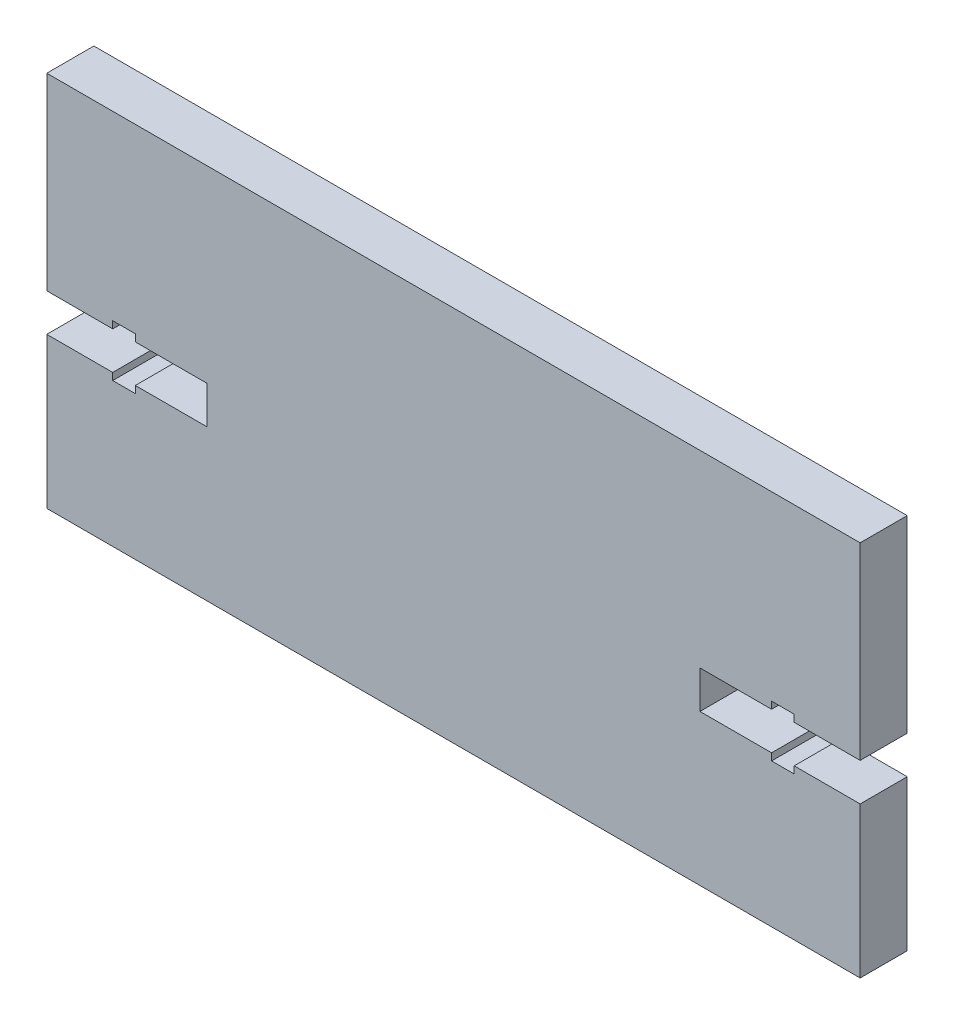
SolidWorks part; units mm, degrees
ref_plane "Front Plane" through (0, 0, 0) normal (0, 0, 1) x (1, 0, 0)
ref_plane "Top Plane" through (0, 0, 0) normal (0, 1, 0) x (1, 0, 0)
ref_plane "Right Plane" through (0, 0, 0) normal (1, 0, 0) x (0, 0, -1)
sketch "Sketch1" plane through (0, 0, 0) normal (0, 0, 1) x (1, 0, 0)
  line L1 (-34.7186, 10.5285) -> (51.6079, 10.5285)
  line L2 (-34.7186, 10.5285) -> (-34.7186, -29.4715)
  line L3 (-34.7186, -29.4715) -> (51.6079, -29.4715)
  line L4 (51.6079, 10.5285) -> (51.6079, -29.4715)
  line L7 (-34.7186, -29.4715) -> (-34.7186, 10.5285) construction
  line L8 (-39.7186, 10.5285) -> (-34.7186, 10.5285) construction
extrude "Boss-Extrude1" add sketch "Sketch1" along normal blind 5
sketch "Sketch2" plane through (0, 0, 0) normal (0, 0, -1) x (-1, 0, 0)
  line L9 (-8.4447, 10.5285) -> (-8.4447, -29.4715) construction
  line L10 (-51.6079, 10.5285) -> (34.7186, 10.5285) construction
  line L50 (34.7186, -29.4715) -> (-51.6079, -29.4715) construction
  line L51 (-51.6079, -29.4715) -> (-51.6079, 10.5285) construction
  line L52 (-51.6079, -9.4715) -> (34.7186, -9.4715) construction
  line L53 (34.7186, 10.5285) -> (34.7186, -29.4715) construction
  line L54 (-51.6079, -9.4715) -> (-44.6079, -9.4715)
  line L55 (-34.6079, -9.4715) -> (-34.6079, -13.4715)
  line L56 (-34.6079, -13.4715) -> (-42.2079, -13.4715)
  line L57 (-44.6079, -9.4715) -> (-44.6079, -8.7215)
  line L58 (-44.6079, -8.7215) -> (-42.2079, -8.7215)
  line L59 (-42.2079, -8.7215) -> (-42.2079, -9.4715)
  line L60 (-42.2079, -13.4715) -> (-42.2079, -14.2215)
  line L61 (-42.2079, -14.2215) -> (-44.6079, -14.2215)
  line L62 (-44.6079, -14.2215) -> (-44.6079, -13.4715)
  line L63 (-42.2079, -9.4715) -> (-34.6079, -9.4715)
  line L64 (-44.6079, -13.4715) -> (-51.6079, -13.4715)
  line L65 (-51.6079, -9.4715) -> (-51.6079, -13.4715)
  line L66 (34.7186, -9.4715) -> (34.7186, -13.4715)
  line L67 (27.7186, -13.4715) -> (34.7186, -13.4715)
  line L68 (25.3186, -9.4715) -> (17.7186, -9.4715)
  line L69 (27.7186, -14.2215) -> (27.7186, -13.4715)
  line L70 (25.3186, -14.2215) -> (27.7186, -14.2215)
  line L71 (25.3186, -13.4715) -> (25.3186, -14.2215)
  line L72 (25.3186, -8.7215) -> (25.3186, -9.4715)
  line L73 (27.7186, -8.7215) -> (25.3186, -8.7215)
  line L74 (27.7186, -9.4715) -> (27.7186, -8.7215)
  line L75 (17.7186, -13.4715) -> (25.3186, -13.4715)
  line L76 (17.7186, -9.4715) -> (17.7186, -13.4715)
  line L77 (34.7186, -9.4715) -> (27.7186, -9.4715)
  point P32 (31.2186, -9.4715)
  dimension "D1" = 0
extrude "Cut-Extrude1" cut sketch "Sketch2" against normal blind 10
